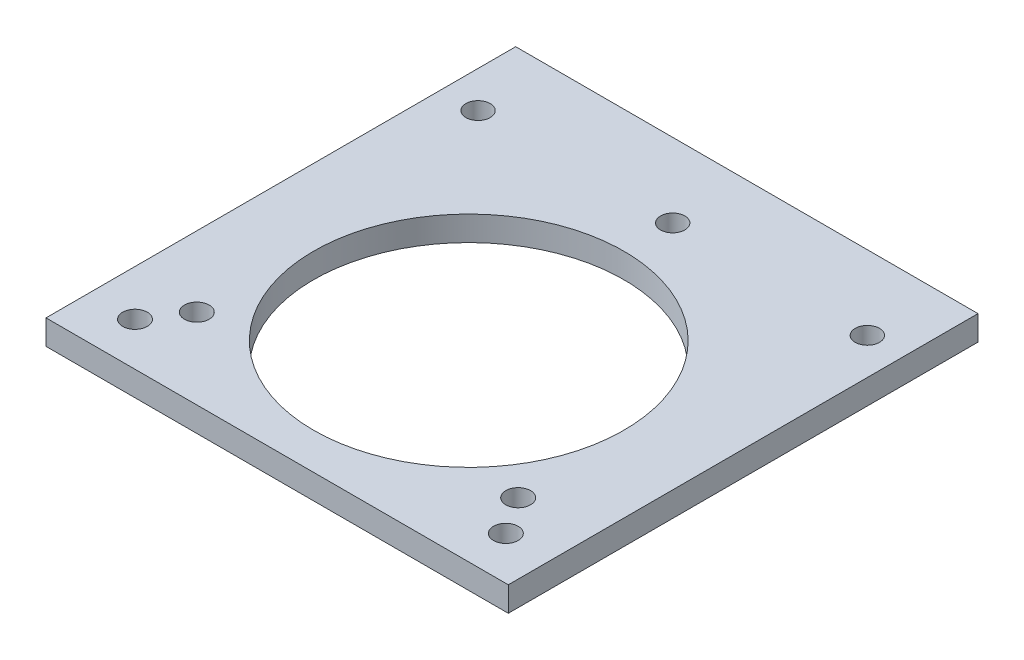
SolidWorks part; units mm, degrees
material "6061 Alloy"
ref_plane "Front Plane" through (0, 0, 0) normal (0, 0, 1) x (1, 0, 0)
ref_plane "Top Plane" through (0, 0, 0) normal (0, 1, 0) x (1, 0, 0)
ref_plane "Right Plane" through (0, 0, 0) normal (1, 0, 0) x (0, 0, -1)
sketch "Sketch2" plane through (0, 0, 0) normal (0, 1, 0) x (1, 0, 0)
  line L0 (0, 0) -> (0, 35.56) construction
  line L1 (-47.5, -60.96) -> (-47.5, 35.56)
  line L2 (47.5, -60.96) -> (47.5, 35.56)
  line L3 (-47.5, 35.56) -> (47.5, 35.56)
  line L4 (-47.5, -60.96) -> (47.5, -60.96)
  point P3 (47.5, -12.7)
  point P5 (0, 35.56)
  point P12 (0, -60.96)
  dimension "D1" = 96.52
  dimension "D2" = 95
  dimension "D3" = 12.7
extrude "Boss-Extrude3" add sketch "Sketch2" along normal blind 5.08
sketch "Sketch3" plane through (0, 5.08, 0) normal (0, 1, 0) x (1, 0, 0)
  line L0 (47.5, 35.56) -> (-47.5, 35.56) construction
  circle A1 centre (0, -21.59) radius 31.88
  dimension "D2" = 63.76
  dimension "D3" = 57.15
extrude "Cut-Extrude1" cut sketch "Sketch3" against normal through all
sketch "Sketch4" plane through (0, 5.08, 0) normal (0, 1, 0) x (1, 0, 0)
  line L0 (47.5, 35.56) -> (-47.5, 35.56) construction
  line L1 (0, 35.56) -> (0, 55.3884) construction
  point P0 (-40, 20.32)
  point P7 (40, 20.32)
  point P8 (0, 20.32)
  point P10 (0, 20.32)
  dimension "D1" = 15.24
  dimension "D2" = 80
hole_wizard "M6x1.0 Tapped Hole1" positions "Sketch4" profile "Sketch6" tap size "M6x1.0" standard "ANSI Metric"
sketch "Sketch6" plane through (-40, 5.08, -20.32) normal (1, 0, 0) x (0, 0, 1)
  line L0 (0, 0) -> (0, 6.5822)
  line L1 (0, 6.5822) -> (2.5, 5.08)
  line L2 (2.5, 5.08) -> (2.5, 0)
  line L5 (2.5, 0) -> (0, 0)
  line L10 (0, 6.5822) -> (-2.5, 5.08) construction
  line L11 (0, -6.35) -> (0, 107.95) construction
  dimension "Tap Drill Dia." = 5
  dimension "Tap Drill Depth" = 5.08
  dimension "Drill Angle" = 118
sketch "Sketch7" plane through (0, 5.08, 0) normal (0, 1, 0) x (1, 0, 0)
  line L0 (0, 0) -> (0, -60.96) construction
  line L1 (-47.5, -60.96) -> (47.5, -60.96) construction
  circle A0 centre (-33.02, -44.45) radius 2.54
  circle A1 centre (33.02, -44.45) radius 2.54
  circle A2 centre (-38.1, -52.07) radius 2.54
  circle A3 centre (38.1, -52.07) radius 2.54
  dimension "D3" = 5.08
  dimension "D4" = 5.08
  dimension "D1" = 44.45
  dimension "D2" = 33.02
  dimension "D5" = 38.1
  dimension "D6" = 7.62
extrude "Cut-Extrude2" cut sketch "Sketch7" against normal blind 7.62
